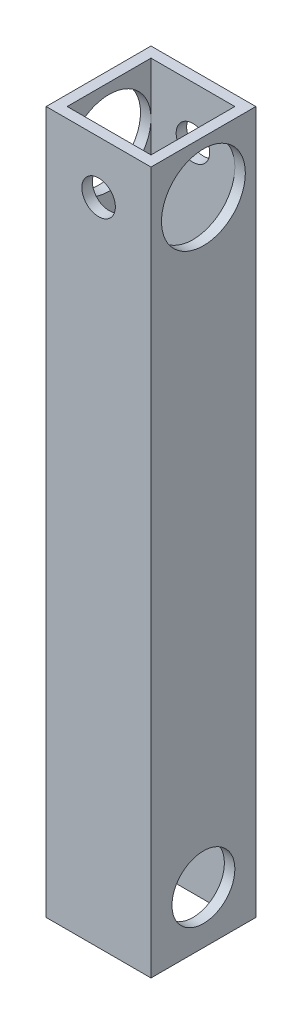
SolidWorks part; units mm, degrees
material "5052-H34"
ref_plane "正面" through (0, 0, 0) normal (0, 0, 1) x (1, 0, 0)
ref_plane "平面" through (0, 0, 0) normal (0, 1, 0) x (1, 0, 0)
ref_plane "右側面" through (0, 0, 0) normal (1, 0, 0) x (0, 0, -1)
sketch "ｽｹｯﾁ1" plane through (0, 0, 0) normal (0, 1, 0) x (1, 0, 0)
  line L1 (0, 0) -> (10, 0)
  line L2 (0, 0) -> (0, 10)
  line L3 (0, 10) -> (10, 10)
  line L4 (10, 0) -> (10, 10)
  dimension "D1" = 10
  dimension "D2" = 10
extrude "押し出し-薄板1" add sketch "ｽｹｯﾁ1" along normal blind 67 thin thin type one direction reverse wall 1
sketch "ｽｹｯﾁ2" plane through (0, 0, 0) normal (0, 0, 1) x (1, 0, 0)
  line L0 (5, 67) -> (5, 0) construction
  line L1 (0, 67) -> (10, 67) construction
  line L2 (0, 0) -> (10, 0) construction
  circle A2 centre (5, 62) radius 1.6
  dimension "D4" = 3.2
  dimension "D5" = 5
extrude "ｶｯﾄ - 押し出し1" cut sketch "ｽｹｯﾁ2" against normal up to surface (10 mm away) up to face at (5, 33.5, -10)
sketch "ｽｹｯﾁ3" plane through (10, 0, 0) normal (1, 0, 0) x (0, 0, -1)
  line L0 (5, 67) -> (5, 0) construction
  line L1 (0, 67) -> (10, 67) construction
  line L2 (0, 0) -> (10, 0) construction
  circle A0 centre (5, 62) radius 4
  circle A2 centre (5, 5) radius 3
  dimension "D1" = 8
  dimension "D2" = 5
  dimension "D3" = 6
  dimension "D4" = 5
extrude "ｶｯﾄ - 押し出し2" cut sketch "ｽｹｯﾁ3" against normal up to surface (10 mm away) up to face at (0, 33.5, -5)
